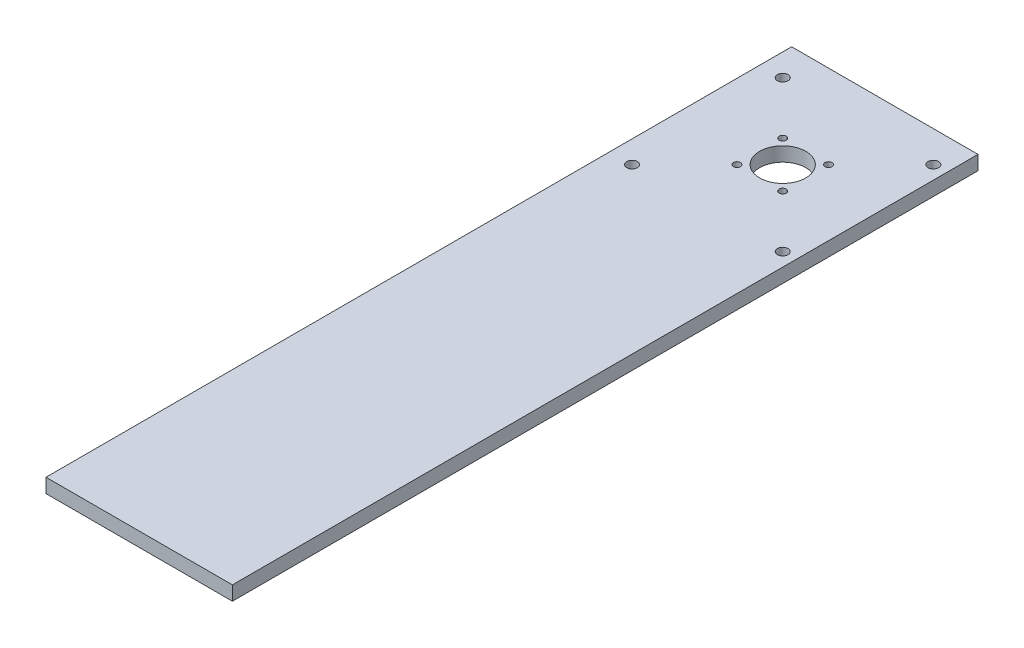
SolidWorks part; units mm, degrees
ref_plane "Front Plane" through (0, 0, 0) normal (0, 0, 1) x (1, 0, 0)
ref_plane "Top Plane" through (0, 0, 0) normal (0, 1, 0) x (1, 0, 0)
ref_plane "Right Plane" through (0, 0, 0) normal (1, 0, 0) x (0, 0, -1)
sketch "Sketch1" plane through (0, 0, 0) normal (0, 1, 0) x (1, 0, 0)
  line L0 (0, 210) -> (0, -210) construction
  line L1 (-55, -210) -> (50, -210)
  line L2 (-55, -210) -> (-55, 210)
  line L3 (-55, 210) -> (50, 210)
  line L4 (50, -210) -> (50, 210)
  line L5 (95, 240) -> (95, -240) construction
  line L6 (-55, 105.3959) -> (50, 105.3959) construction
  line L7 (-44.628, 210) -> (-44.628, -210) construction
  line L8 (38.5879, 210) -> (38.5879, -210) construction
  line L9 (-55, -78.4291) -> (50, -78.4291) construction
  line L10 (-42.4264, 107.5736) -> (0, 150) construction
  line L11 (-12.9047, 137.0953) -> (0, 150) construction
  circle A0 centre (0, 150) radius 50 construction
  circle A1 centre (0, 150) radius 13
  circle A2 centre (-42.4264, 107.5736) radius 3
  circle A3 centre (-42.4264, 192.4264) radius 3
  circle A4 centre (42.4264, 192.4264) radius 3
  circle A5 centre (42.4264, 107.5736) radius 3
  circle A6 centre (-12.9047, 137.0953) radius 2
  circle A7 centre (-12.9047, 162.9047) radius 2
  circle A8 centre (12.9047, 162.9047) radius 2
  circle A9 centre (12.9047, 137.0953) radius 2
  point P31 (0, 150)
  point P40 (0, 150)
  dimension "D1" = 100
  dimension "D2" = 95
  dimension "D10" = 6
  dimension "D12" = 26
  dimension "D13" = 4
  dimension "D3" = 150
  dimension "D4" = 420
  dimension "D5" = 45
  dimension "D6" = 60
  dimension "D7" = 105
  dimension "D8" = 60
  dimension "D9" = 45
  dimension "D14" = 18.25
  dimension "D16" = 45
  dimension "D11" = 4
  dimension "D15" = 4
extrude "Boss-Extrude1" add sketch "Sketch1" along normal blind 8
